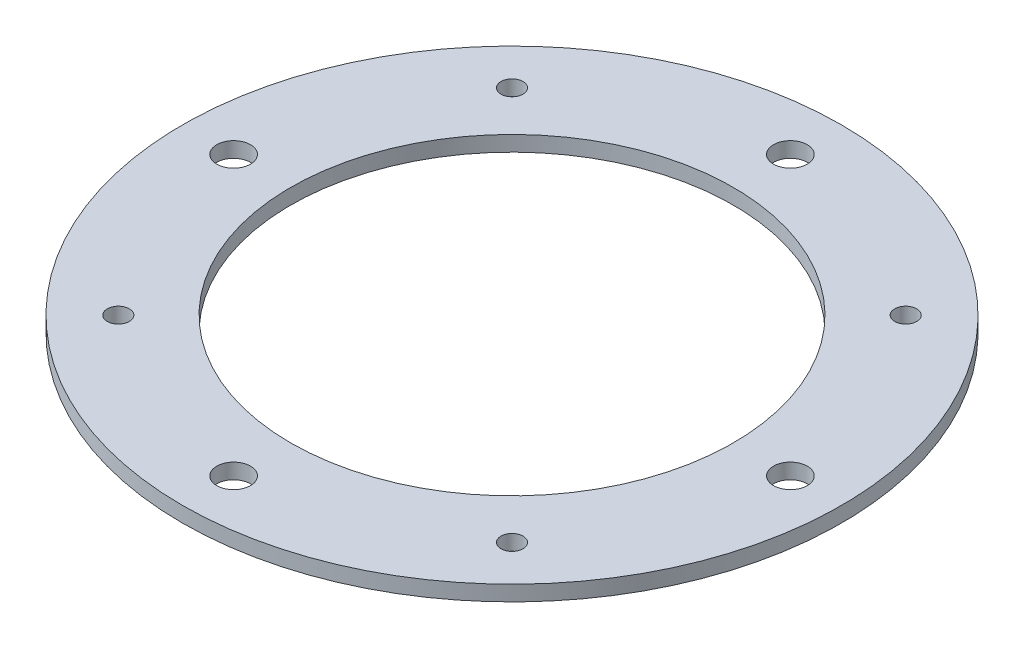
SolidWorks part; units mm, degrees
ref_plane "Front Plane" through (0, 0, 0) normal (0, 0, 1) x (1, 0, 0)
ref_plane "Top Plane" through (0, 0, 0) normal (0, 1, 0) x (1, 0, 0)
ref_plane "Right Plane" through (0, 0, 0) normal (1, 0, 0) x (0, 0, -1)
sketch "Sketch1" plane through (0, 0, 0) normal (0, 1, 0) x (1, 0, 0)
  circle A0 centre (0, 0) radius 64.4
  dimension "Diameter" = 128.8
extrude "Boss-Extrude1" add sketch "Sketch1" along normal mid plane 3
hole_wizard "M6 Clearance Hole1" positions "Sketch8" profile "Sketch9" hole size "M6" standard "ANSI Metric" end condition up to next
sketch "Sketch8" plane through (0, 1.5, 0) normal (0, 1, 0) x (1, 0, 0)
  line L0 (0, 0) -> (54.4, 0) construction
  point P0 (54.4, 0)
  dimension "ThreadedHoleDistance" = 54.4
sketch "Sketch9" plane through (54.4, 1.5, 0) normal (1, 0, 0) x (0, 0, 1)
  line L0 (0, 0) -> (0, 3)
  line L1 (0, 3) -> (3.3, 3)
  line L2 (3.3, 3) -> (3.3, 0)
  line L5 (3.3, 0) -> (0, 0)
  line L11 (0, -6.35) -> (0, 107.95) construction
  dimension "Thru Hole Dia." = 6.6
  dimension "Thru Hole Depth" = 3
pattern_circular "CirPattern2" count 4 over 360 about axis through (0, 0, 0) along (0, 1, 0) of "M6 Clearance Hole1"
sketch "Sketch5" plane through (0, 1.5, 0) normal (0, 1, 0) x (1, 0, 0)
  line L0 (0, 0) -> (64.4, 0) construction
  line L2 (0, 0) -> (38.4666, 38.4666) construction
  circle A0 centre (0, 0) radius 64.4 construction
  dimension "D1" = 45
  dimension " NoseShellHoleRadius" = 54.4
hole_wizard "M4 Clearance Hole1" positions "Sketch6" profile "Sketch7" hole size "M4" standard "ANSI Metric" end condition up to next
sketch "Sketch6" plane through (0, 1.5, 0) normal (0, 1, 0) x (1, 0, 0)
  point P0 (38.4666, 38.4666)
sketch "Sketch7" plane through (38.4666, 1.5, -38.4666) normal (1, 0, 0) x (0, 0, 1)
  line L0 (0, 0) -> (0, 3)
  line L1 (0, 3) -> (2.15, 3)
  line L2 (2.15, 3) -> (2.15, 0)
  line L5 (2.15, 0) -> (0, 0)
  line L11 (0, -6.35) -> (0, 107.95) construction
  dimension "Thru Hole Dia." = 4.3
  dimension "Thru Hole Depth" = 3
pattern_circular "CirPattern1" count 4 over 360 about axis through (0, 0, 0) along (0, 1, 0) of "M4 Clearance Hole1"
sketch "Sketch10" plane through (0, 1.5, 0) normal (0, 1, 0) x (1, 0, 0)
  circle A0 centre (0, 0) radius 43.25
  dimension "D1" = 86.5
extrude "Cut-Extrude1" cut sketch "Sketch10" against normal through all
